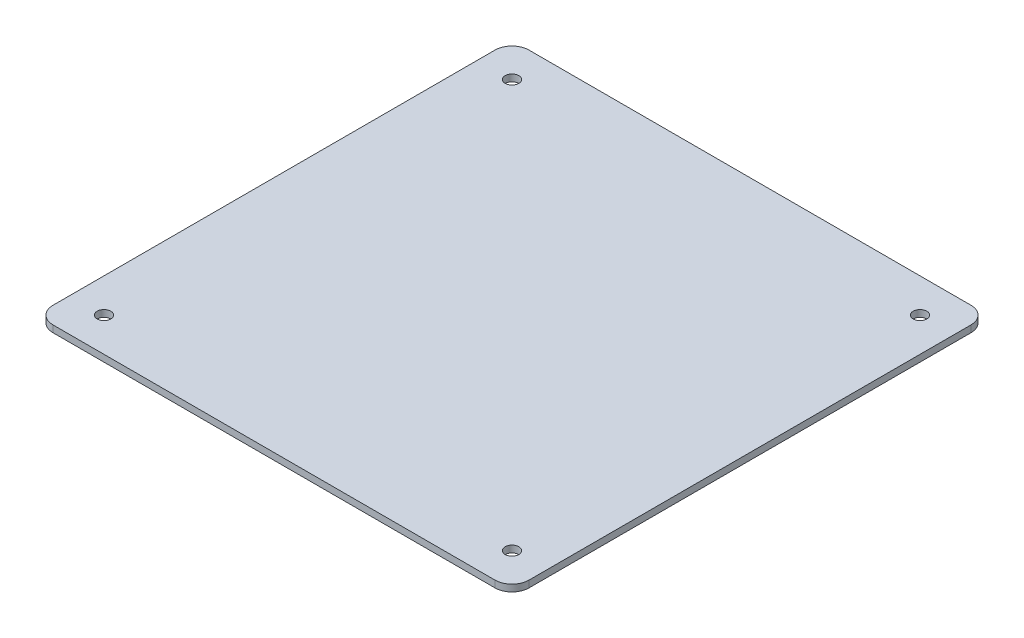
SolidWorks part; units mm, degrees
material "3.0205 (EN-AW 1200)"
ref_plane "Płaszczyzna przednia" through (0, 0, 0) normal (0, 0, 1) x (1, 0, 0)
ref_plane "Płaszczyzna górna" through (0, 0, 0) normal (0, 1, 0) x (1, 0, 0)
ref_plane "Płaszczyzna prawa" through (0, 0, 0) normal (1, 0, 0) x (0, 0, -1)
sketch "Szkic1" plane through (0, 0, 0) normal (0, 1, 0) x (1, 0, 0)
  line L1 (-130, -140) -> (130, -140)
  line L2 (-140, -130) -> (-140, 130)
  line L3 (-130, 140) -> (130, 140)
  line L4 (140, -130) -> (140, 130)
  line L5 (-140, -140) -> (140, 140) construction
  line L6 (-140, 140) -> (140, -140) construction
  arc A0 (-140, 130) -> (-130, 140) centre (-130, 130) cw
  arc A1 (-130, -140) -> (-140, -130) centre (-130, -130) cw
  arc A2 (130, -140) -> (140, -130) centre (130, -130) ccw
  arc A3 (130, 140) -> (140, 130) centre (130, 130) cw
  point P0 (0, 0)
  dimension "D3" = 10
  dimension "D1" = 280
  dimension "D2" = 280
extrude "Dodanie-wyciągnięcie1" add sketch "Szkic1" along normal blind 4
sketch "Szkic2" plane through (0, 4, 0) normal (0, 1, 0) x (1, 0, 0)
  line L0 (130, 140) -> (-130, 140) construction
  line L1 (140, -130) -> (140, 130) construction
  circle A0 centre (120, 120) radius 4
  circle A1 centre (120, -120) radius 4
  circle A2 centre (-120, -120) radius 4
  circle A3 centre (-120, 120) radius 4
  point P6 (94.4648, -211.2529)
  point P7 (0, 0)
  point P15 (0, 0)
  dimension "D1" = 8
  dimension "D2" = 20
  dimension "D3" = 20
  dimension "D4" = 4
extrude "Wytnij-wyciągnięcie1" cut sketch "Szkic2" against normal through all
